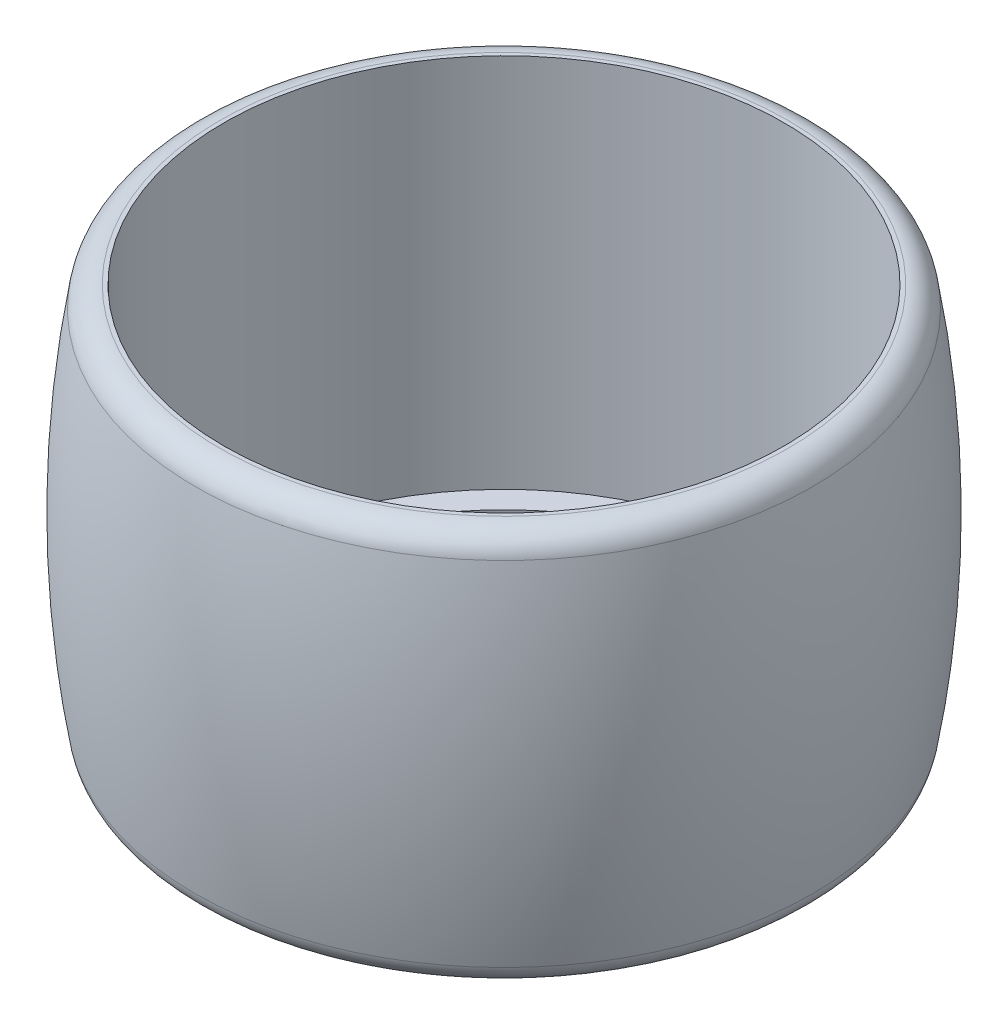
SolidWorks part; units mm, degrees
material "POLYURETHANE (11671)"
ref_plane "Front Plane" through (0, 0, 0) normal (0, 0, 1) x (1, 0, 0)
ref_plane "Top Plane" through (0, 0, 0) normal (0, 1, 0) x (1, 0, 0)
ref_plane "Right Plane" through (0, 0, 0) normal (1, 0, 0) x (0, 0, -1)
sketch "Sketch1" plane through (0, 0, 0) normal (0, 0, 1) x (1, 0, 0)
  line L8 (0, 7.386) -> (0, -6.378) construction
  line L9 (-7.6015, 0) -> (9.1971, 0) construction
  line L10 (20.45, -14.3) -> (22.45, -14.3)
  line L11 (22.45, -14.3) -> (22.45, 15.8)
  line L14 (22.45, 15.8) -> (24.45, 15.8)
  line L16 (24.45, -15.8) -> (20.45, -15.8)
  line L17 (20.45, -15.8) -> (20.45, -14.3)
  arc A0 (24.45, 15.8) -> (24.45, -15.8) centre (-60, 0) cw
  point P6 (17.45, 16.5117)
  point P9 (0, 0)
  point P15 (0, 0)
other "Pen Sketch1" parameters "D1"=70.898, "D2"=12.5015, "D3"=28.2028, "D4"=34.9, "D5"=3, "D6"=22.6476
revolve "Revolve3" add sketch "Sketch1" angle 360 about L8
fillet "Fillet1" radius 2 2 edges at (0, -15.8, 24.45) (0, 15.8, 24.45)
